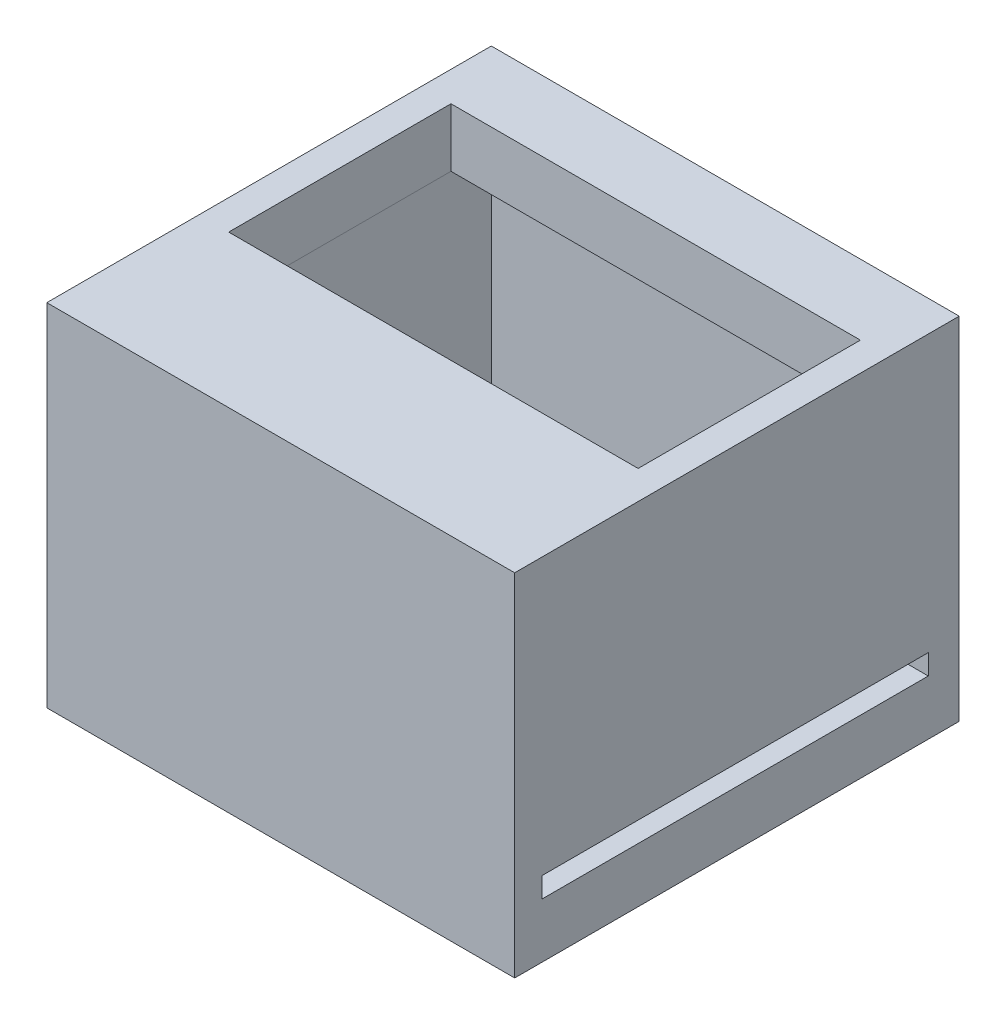
SolidWorks part; units mm, degrees
ref_plane "Front Plane" through (0, 0, 0) normal (0, 0, 1) x (1, 0, 0)
ref_plane "Top Plane" through (0, 0, 0) normal (0, 1, 0) x (1, 0, 0)
ref_plane "Right Plane" through (0, 0, 0) normal (1, 0, 0) x (0, 0, -1)
sketch "Sketch1" plane through (0, 0, 0) normal (0, 1, 0) x (1, 0, 0)
  line L1 (-19.2258, 12.5806) -> (20.7742, 12.5806)
  line L2 (-19.2258, 12.5806) -> (-19.2258, -25.4194)
  line L3 (-19.2258, -25.4194) -> (20.7742, -25.4194)
  line L4 (20.7742, 12.5806) -> (20.7742, -25.4194)
  dimension "D1" = 40
  dimension "D2" = 38
extrude "Boss-Extrude2" add sketch "Sketch1" along normal blind 30
sketch "Sketch3" plane through (0, 0, 0) normal (0, 1, 0) x (1, 0, 0)
  line L0 (-19.2258, -25.4194) -> (20.7742, -25.4194) construction
  line L1 (-16.7258, 10.0806) -> (18.2742, 10.0806)
  line L2 (-16.7258, 10.0806) -> (-16.7258, -22.9194)
  line L3 (-16.7258, -22.9194) -> (18.2742, -22.9194)
  line L4 (18.2742, 10.0806) -> (18.2742, -22.9194)
  line L5 (20.7742, 12.5806) -> (-19.2258, 12.5806) construction
  line L6 (-19.2258, 12.5806) -> (-19.2258, -25.4194) construction
  line L7 (20.7742, -25.4194) -> (20.7742, 12.5806) construction
  dimension "D1" = 33
  dimension "D2" = 35
  dimension "D3" = 2.5
  dimension "D4" = 2.5
  dimension "D5" = 2.5
  dimension "D6" = 2.5
extrude "Cut-Extrude1" cut sketch "Sketch3" along normal blind 25
sketch "Sketch4" plane through (0, 0, 0) normal (0, 1, 0) x (1, 0, 0)
  line L0 (18.2742, 10.0806) -> (-16.7258, 10.0806) construction
  line L1 (-16.6737, 6.5806) -> (18.3263, 6.5806)
  line L2 (-16.6737, 6.5806) -> (-16.6737, -12.4194)
  line L3 (-16.6737, -12.4194) -> (18.3263, -12.4194)
  line L4 (18.3263, 6.5806) -> (18.3263, -12.4194)
  point P6 (0.7742, 10.0806)
  dimension "D1" = 19
  dimension "D2" = 35
  dimension "D3" = 3.5
extrude "Cut-Extrude3" cut sketch "Sketch4" along normal blind 30 contours L2 L1 L4 L3
sketch "Sketch5" plane through (0, 0, 0) normal (1, 0, 0) x (0, 0, -1)
  line L5 (-23.0967, 4.6803) -> (9.9366, 4.6803)
  line L6 (-23.0967, 4.6803) -> (-23.0967, 6.4136)
  line L7 (-23.0967, 6.4136) -> (9.9366, 6.4136)
  line L8 (9.9366, 4.6803) -> (9.9366, 6.4136)
extrude "Cut-Extrude4" cut sketch "Sketch5" along normal blind 100 from surface at -79.2258
